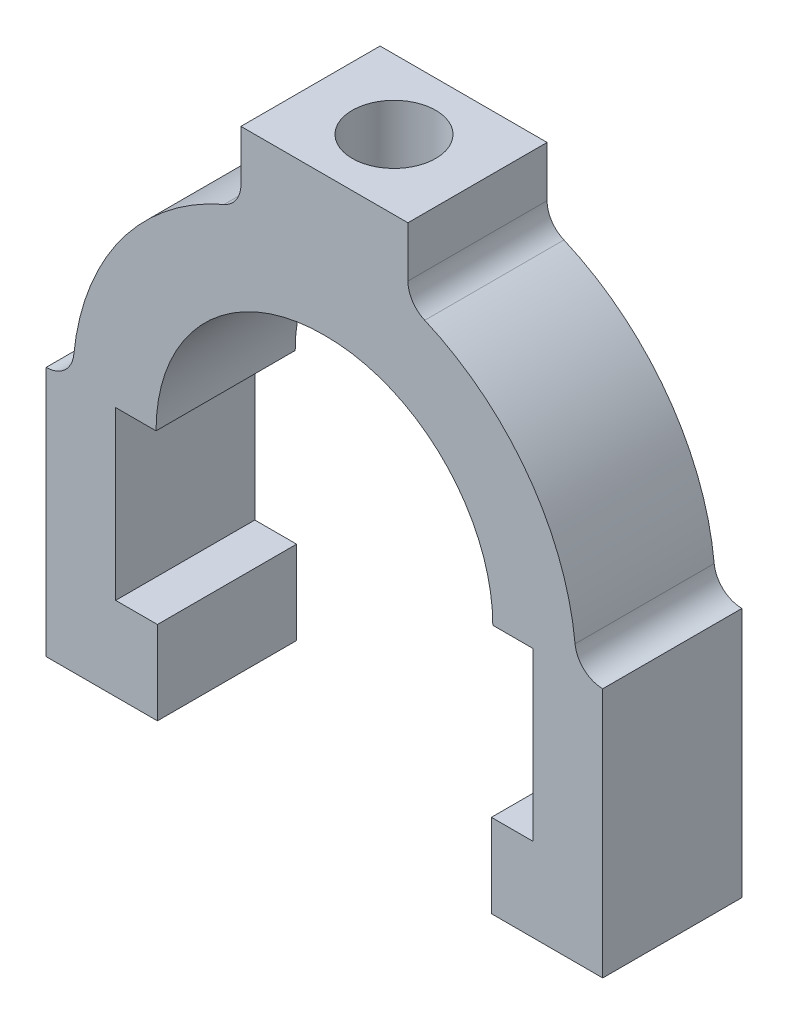
SolidWorks part; units mm, degrees
material "1060 Alloy"
ref_plane "Front Plane" through (0, 0, 0) normal (0, 0, 1) x (1, 0, 0)
ref_plane "Top Plane" through (0, 0, 0) normal (0, 1, 0) x (1, 0, 0)
ref_plane "Right Plane" through (0, 0, 0) normal (1, 0, 0) x (0, 0, -1)
sketch "Sketch2" plane through (0, 0, 0) normal (0, 0, 1) x (1, 0, 0)
  line L0 (28, 72.7475) -> (28, 80)
  line L1 (16, 12) -> (16, 0)
  line L2 (16, 0) -> (0, 0)
  line L3 (0, 0) -> (0, 36)
  line L4 (16, 12) -> (10, 12)
  line L5 (28, 80) -> (52, 80)
  line L6 (40, 80) -> (40, -9.0381) construction
  line L7 (10, 12) -> (10, 36)
  line L8 (10, 36) -> (15.7995, 36)
  line L9 (70, 36) -> (64.2005, 36)
  line L10 (70, 12) -> (70, 36)
  line L11 (64, 12) -> (70, 12)
  line L12 (80, 0) -> (80, 36)
  line L13 (64, 0) -> (80, 0)
  line L14 (64, 12) -> (64, 0)
  line L15 (52, 72.7475) -> (52, 80)
  arc A0 (0, 36) -> (3.9799, 39.6) centre (0, 40) ccw
  arc A1 (3.9799, 39.6) -> (25.5799, 69.0727) centre (39.7995, 36) cw
  arc A2 (25.5799, 69.0727) -> (28, 72.7475) centre (24, 72.7475) ccw
  arc A3 (15.7995, 36) -> (40, 59.9992) centre (39.7995, 36) cw
  arc A4 (64.2005, 36) -> (40, 59.9992) centre (40.2005, 36) ccw
  arc A5 (54.4201, 69.0727) -> (52, 72.7475) centre (56, 72.7475) cw
  arc A6 (76.0201, 39.6) -> (54.4201, 69.0727) centre (40.2005, 36) ccw
  arc A7 (80, 36) -> (76.0201, 39.6) centre (80, 40) cw
  dimension "D5" = 4
  dimension "D6" = 36
  dimension "D7" = 4
  dimension "D9" = 24
  dimension "D1" = 16
  dimension "D2" = 12
  dimension "D3" = 10
  dimension "D4" = 24
  dimension "D8" = 80
  dimension "D10" = 36
  dimension "D11" = 12
  dimension "D12" = 40
extrude "Boss-Extrude1" add sketch "Sketch2" against normal blind 20
sketch "Sketch3" plane through (0, 80, 0) normal (0, 1, 0) x (1, 0, 0)
  line L0 (52, 20) -> (52, 0) construction
  line L1 (52, 20) -> (28, 20) construction
  circle A0 centre (40, 10) radius 6
  dimension "D1" = 12
  dimension "D2" = 12
  dimension "D3" = 10
extrude "Cut-Extrude1" cut sketch "Sketch3" against normal through all
